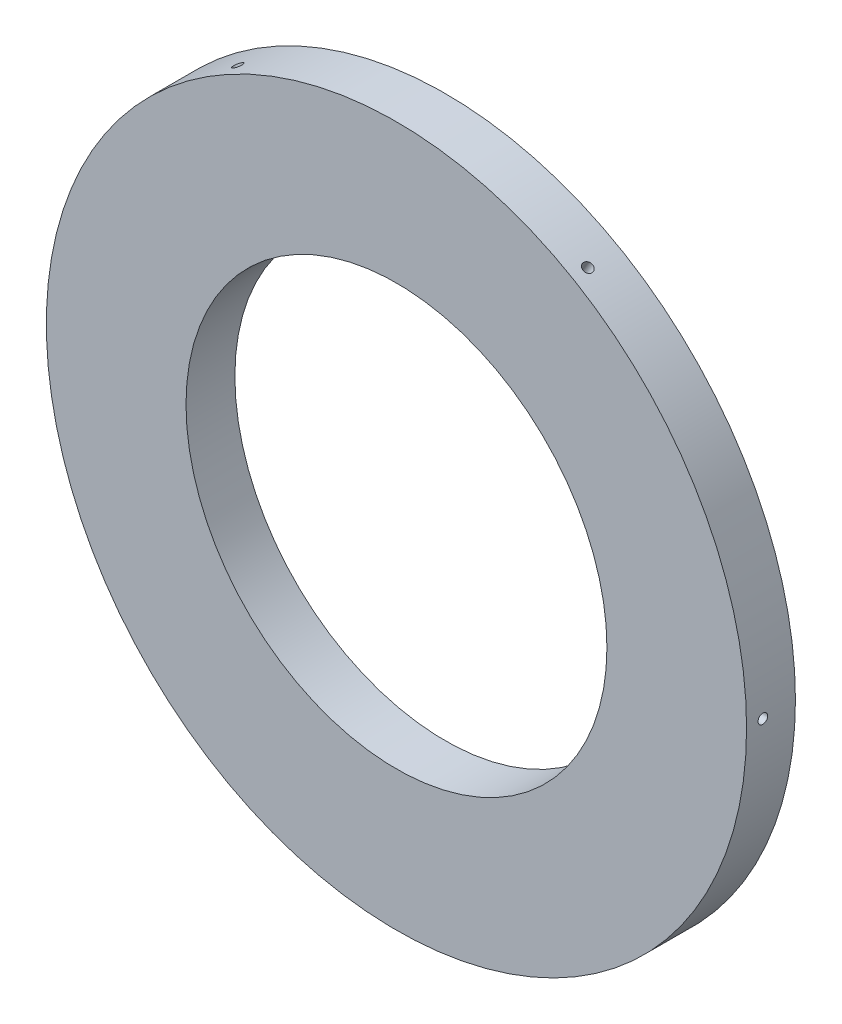
SolidWorks part; units mm, degrees
material "6061-T6 (SS)"
ref_plane "Front" through (0, 0, 0) normal (0, 0, 1) x (1, 0, 0)
ref_plane "Top" through (0, 0, 0) normal (0, 1, 0) x (1, 0, 0)
ref_plane "Right" through (0, 0, 0) normal (1, 0, 0) x (0, 0, -1)
sketch "Sketch1" plane through (0, 0, 0) normal (0, 0, 1) x (1, 0, 0)
  circle A0 centre (0, 0) radius 81.8896
  circle A1 centre (0, 0) radius 49.2252
  dimension "D1" = 163.7792
  dimension "D2" = 98.4504
extrude "Boss-Extrude1" add sketch "Sketch1" along normal blind 11.43
hole_wizard "#4-40 Tapped Hole1" positions "3DSketch1" profile "Sketch2" tap size "#4-40" standard "ANSI Inch"
sketch3d "3DSketch1"
  point P0 (81.8896, 0, 7.62)
  dimension "D1" = 3.81
sketch "Sketch2" plane through (81.8896, 0, 7.62) normal (0, 1, 0) x (0, 0, -1)
  line L0 (0, 0) -> (0, 8.2738)
  line L1 (0, 8.2738) -> (1.1303, 7.5946)
  line L2 (1.1303, 7.5946) -> (1.1303, 0)
  line L5 (1.1303, 0) -> (0, 0)
  line L10 (0, 8.2738) -> (-1.1303, 7.5946) construction
  line L11 (0, -6.35) -> (0, 107.95) construction
  dimension "Tap Drill Dia." = 2.2606
  dimension "Tap Drill Depth" = 7.5946
  dimension "Drill Angle" = 118
cosmetic thread "Hole Thread1" parameters "D1"=5.6896, "D2"=2.8448
pattern_circular "CirPattern1" count 6 over 360 about axis through (0, 0, 11.43) along (0, 0, -1) of "#4-40 Tapped Hole1"
sketch "Sketch3" plane through (0, 0, 0) normal (0, 0, 1) x (1, 0, 0)
  line L0 (0, 0) -> (81.8896, 0) construction
  line L1 (50.927, 0) -> (81.1276, 0) construction
  line L2 (50.8544, -2.7178) -> (81.0821, -2.7178)
  line L3 (0, 0) -> (40.9448, 70.9185) construction
  line L4 (50.8544, 2.7178) -> (81.0821, 2.7178)
  line L5 (50.927, 2.7178) -> (81.1276, 2.7178) construction
  line L6 (50.927, -2.7178) -> (81.1276, -2.7178) construction
  line L7 (25.4635, 44.1041) -> (40.9448, 70.9185)
  line L8 (27.7809, 42.6823) -> (43.2985, 69.5596)
  line L9 (23.0735, 45.4001) -> (38.5911, 72.2774)
  line L10 (27.8172, 42.7452) -> (43.2985, 69.5596) construction
  line L11 (23.1098, 45.463) -> (38.5911, 72.2774) construction
  circle A0 centre (0, 0) radius 81.8896 construction
  circle A1 centre (0, 0) radius 81.1276
  circle A2 centre (0, 0) radius 50.927
  circle A3 centre (0, 0) radius 81.8896
  arc A4 (41.9198, 70.3466) -> (39.962, 71.4769) centre (0, 0) ccw construction
  arc A5 (41.9198, 70.3466) -> (39.962, 71.4769) centre (0, 0) ccw
  arc A6 (81.8818, -1.1303) -> (81.8818, 1.1303) centre (0, 0) ccw construction
  arc A7 (81.8818, -1.1303) -> (81.8818, 1.1303) centre (0, 0) ccw
  point P45 (0, 0)
  dimension "D1" = 0.762
  dimension "D2" = 60
  dimension "D5" = 2.7178
  dimension "D6" = 101.854
  dimension "D3" = 2.7178
  dimension "D4" = 2.7178
  dimension "D7" = 2.7178
extrude "Cut-Extrude1" cut sketch "Sketch3" along normal blind 10.922 contours L4 A2 L8 A1
fillet "Fillet2" radius 4.9276 2 edges at (42.8947, 68.8602, 5.461) (81.0821, 2.7178, 5.461)
fillet "Fillet4" radius 6.35 2 edges at (27.7809, 42.6823, 5.461) (50.8544, 2.7178, 5.461)
fillet "Fillet3" radius 1.5875 8 edges at (79.4704, 4.3405, 10.922) (66.1851, 2.7178, 10.922) (44.1041, 25.4635, 10.922) (35.4462, 55.9591, 10.922) (43.4942, 66.6532, 10.922) (70.2586, 40.5638, 10.922) (52.4353, 4.2353, 10.922) (29.8855, 43.2926, 10.922)
pattern_circular "CirPattern2" count 6 over 360 about axis through (0, 0, 0) along (0, 0, 1) of "Cut-Extrude1", "Fillet2", "Fillet3", "Fillet4"
sketch "Sketch4" plane through (0, 0, 0) normal (0, 0, -1) x (-1, 0, 0)
  line L0 (-81.8896, 0) -> (0, 0) construction
  line L1 (0, 0) -> (0, -81.8896) construction
  line L2 (0, -81.8896) -> (-81.8896, -81.8896) construction
  line L3 (-81.8896, -81.8896) -> (-81.8896, 0) construction
  dimension "D1" = 81.8896
  dimension "D2" = 81.8896
ref_plane "Plane1" through (0, 0, 0) normal (0.866, -0.5, 0) x (0, 0, -1)
ref_plane "Plane2" through (0, 0, 0) normal (0.866, 0.5, 0) x (0, 0, -1)
